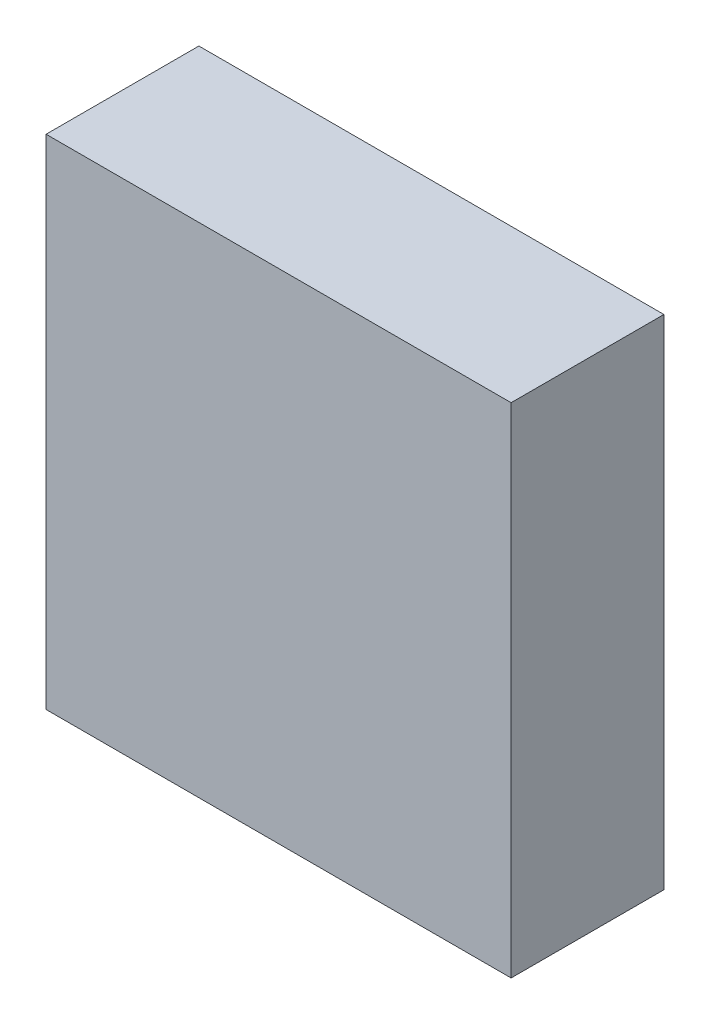
SolidWorks part; units mm, degrees
material "Bateria"
ref_plane "Plano frontal" through (0, 0, 0) normal (0, 0, 1) x (1, 0, 0)
ref_plane "Plano superior" through (0, 0, 0) normal (0, 1, 0) x (1, 0, 0)
ref_plane "Plano direito" through (0, 0, 0) normal (1, 0, 0) x (0, 0, -1)
sketch "Esboço1" plane through (0, 0, 0) normal (0, 0, 1) x (1, 0, 0)
  line L1 (-70.6632, 65.8327) -> (-0.6632, 65.8327)
  line L2 (-70.6632, 65.8327) -> (-70.6632, -9.1673)
  line L3 (-70.6632, -9.1673) -> (-0.6632, -9.1673)
  line L4 (-0.6632, 65.8327) -> (-0.6632, -9.1673)
extrude "Ressalto-extrusão1" add sketch "Esboço1" along normal blind 23
